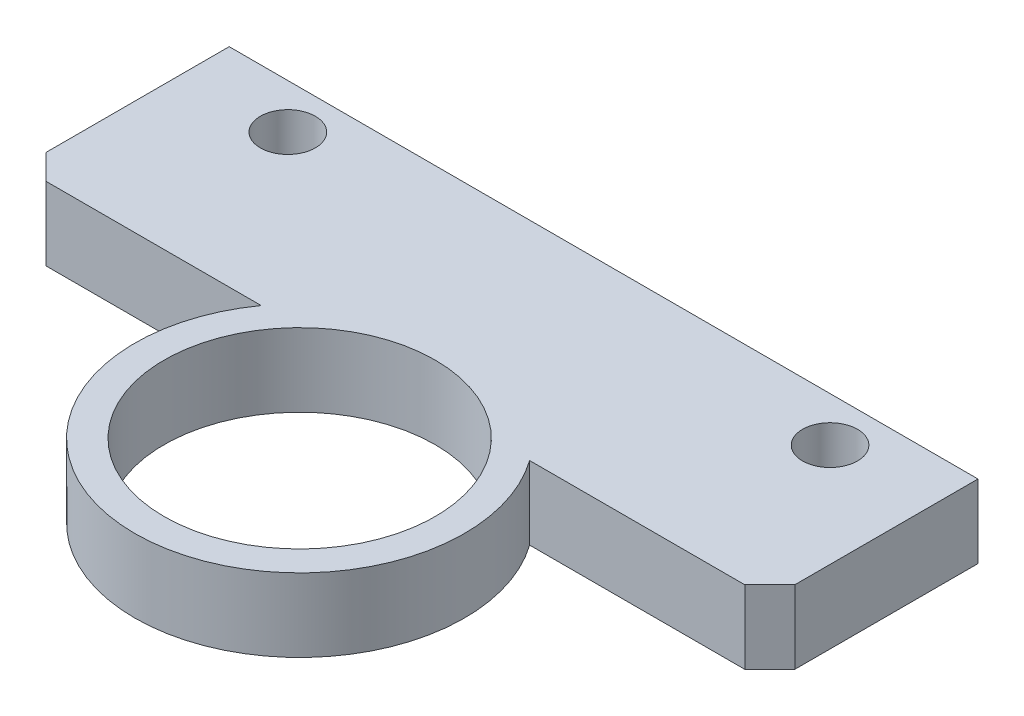
SolidWorks part; units mm, degrees
ref_plane "Front Plane" through (0, 0, 0) normal (0, 0, 1) x (1, 0, 0)
ref_plane "Top Plane" through (0, 0, 0) normal (0, 1, 0) x (1, 0, 0)
ref_plane "Right Plane" through (0, 0, 0) normal (1, 0, 0) x (0, 0, -1)
sketch "Sketch1" plane through (0, 0, 0) normal (0, 1, 0) x (1, 0, 0)
  circle A0 centre (0, 0) radius 18.5
  circle A1 centre (0, 0) radius 22.5
extrude "Boss-Extrude1" add sketch "Sketch1" along normal blind 10
sketch "Sketch2" plane through (0, 0, 0) normal (0, 1, 0) x (1, 0, 0)
  line L0 (37, 13.0661) -> (47.6818, 13.0661)
  line L1 (37, 13.0661) -> (18.3174, 13.0661)
  line L2 (51.0964, 16.4807) -> (51.0964, 41.4807)
  line L3 (51.0964, 41.4807) -> (-51.0964, 41.4807)
  line L4 (47.6818, 13.0661) -> (51.0964, 16.4807)
  line L5 (-37, 13.0661) -> (-18.3174, 13.0661)
  line L6 (-37, 13.0661) -> (-47.6818, 13.0661)
  line L7 (-51.0964, 16.4807) -> (-51.0964, 41.4807)
  line L9 (-47.6818, 13.0661) -> (-51.0964, 16.4807)
  line L10 (-18.3174, 13.0661) -> (-13.0968, 13.0661)
  line L11 (13.0968, 13.0661) -> (18.3174, 13.0661)
  line L12 (0, 41.4807) -> (0, 28.9807)
  circle A0 centre (0, 0) radius 18.5
  circle A5 centre (0, 0) radius 22.5 construction
  circle A6 centre (-37, 35.3877) radius 3.75
  circle A7 centre (37, 35.3877) radius 3.75
extrude "Boss-Extrude2" add sketch "Sketch2" along normal blind 10
